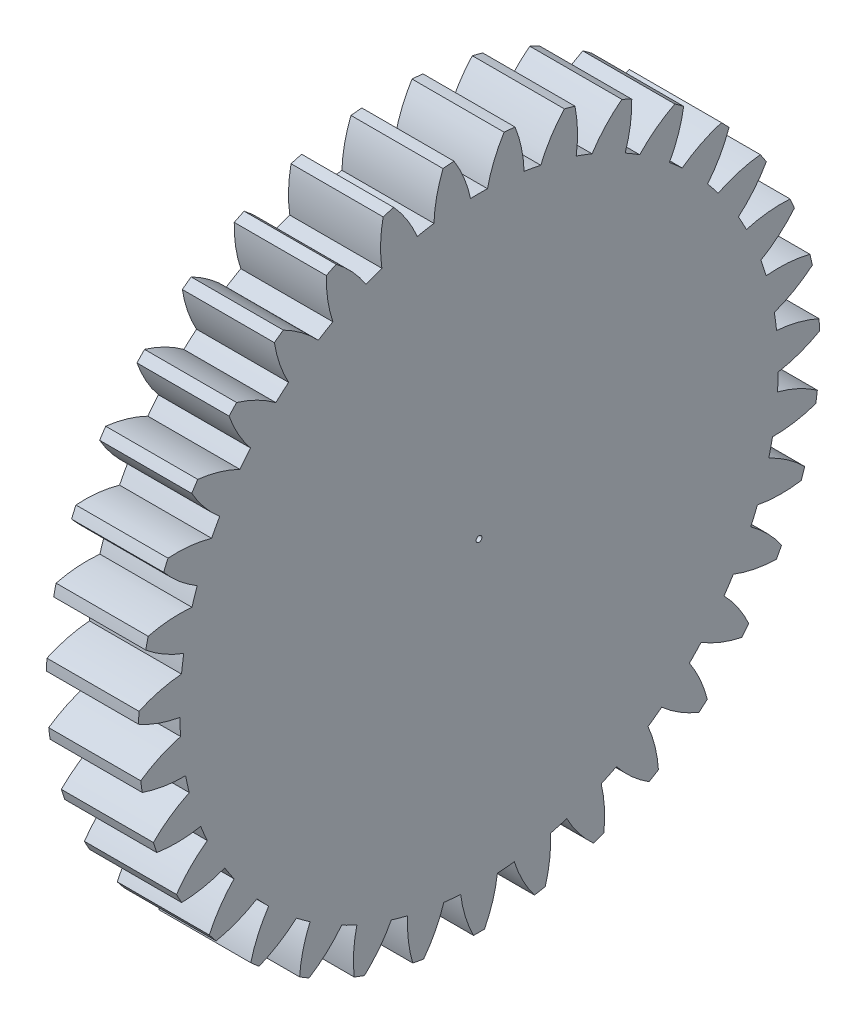
SolidWorks part; units mm, degrees
ref_plane "Plane1" through (0, 0, 0) normal (0, 0, 1) x (1, 0, 0)
ref_plane "Plane2" through (0, 0, 0) normal (0, 1, 0) x (1, 0, 0)
ref_plane "Plane3" through (0, 0, 0) normal (1, 0, 0) x (0, 0, -1)
sketch "HoldingSke" plane through (0, 0, 0) normal (0, 1, 0) x (1, 0, 0)
  line L0 (0, 0) -> (208.0646, -145.6884)
  line L1 (-15, 0) -> (100, 0) construction
  line L2 (0, 0) -> (-2.1039, 2.3779)
  line L3 (0, 0) -> (-11.863, 4.5341)
  line L4 (0, 0) -> (7.0742, 4.9534)
  line L5 (0, 0) -> (-47.5972, -17.7524)
  line L6 (0, 0) -> (-10.5278, -7.1032)
  line L7 (-2.1039, 2.3779) -> (8.8308, 51.9871)
  line L8 (-76.2, 54.61) -> (-75.184, 54.61)
  line L9 (-71.009, 38.7566) -> (-53.1078, 45.2721)
  line L10 (-76.2, 71.12) -> (104.1128, 71.12)
  line L11 (0, 0) -> (-12.7, 0)
  line L12 (-76.2, 101.6) -> (-76.0984, 101.6)
  line L13 (24.9733, 27.94) -> (52.9518, 28.4284)
  line L14 (24.9733, 27.94) -> (24.9746, 27.94)
  line L15 (24.9733, 27.94) -> (100.4006, 29.5858)
  circle A0 centre (0, 0) radius 0.3969
  circle A1 centre (0, 0) radius 38.1
  circle A2 centre (0, 0) radius 38.1
  circle A3 centre (0, 0) radius 0.3969
  dimension "MHD" = 76.2
  dimension "Hub_dia" = 76.2
  dimension "Bore" = 0.7937
  dimension "MBD" = 0.7937
  dimension "Num_teeth" = 35
  dimension "Pitch" = 254
  dimension "Overall_len" = 50.8
  dimension "Show_teeth" = 35
  dimension "Thickness" = 12.7
  dimension "OAL" = 50.8001
  dimension "T_dim" = 1.016
  dimension "Ap" = 20
  dimension "H" = 19.05
  dimension "Pitch_radius" = 180.3128
  dimension "Width" = 12.7
  dimension "Backlash" = 0.1016
  dimension "Addendum_fac" = 1
  dimension "Dedendum_fac" = 1.25
  dimension "Clearance_fac" = 0.25
  dimension "Dedendum_add" = 0.0013
sketch "BasProSke" plane through (0, 0, 0) normal (0, 1, 0) x (1, 0, 0)
  line L0 (-10, 0) -> (60, 0) construction
  line L1 (0, 0) -> (0, 46.99)
  line L2 (0, 0) -> (12.7, 0)
  line L3 (12.7, 0) -> (12.7, 46.99)
  line L4 (12.7, 46.99) -> (0, 46.99)
  dimension "Thickness" = 12.7
  dimension "Diameter" = 93.98
revolve "Base-Revolve" add sketch "BasProSke" angle 360 about L0
sketch "TooCutSke" plane through (0, 0, 0) normal (1, 0, 0) x (0, 0, -1)
  line L1 (0, 0) -> (0, 107) construction
  line L2 (0, 0) -> (-2.172, 44.3969) construction
  line L3 (0, 0) -> (-7.9623, 88.4682) construction
  line L4 (-2.172, 44.3969) -> (-3.9811, 44.2341) construction
  arc A0 (1.1677, 41.2572) -> (-1.1677, 41.2572) centre (0, 0) ccw
  arc A1 (3.4731, 46.8869) -> (-3.4731, 46.8869) centre (0, 0) ccw
  circle A2 centre (0, 0) radius 44.45 construction
  circle A3 centre (0, 0) radius 41.7693 construction
  arc A4 (-1.1677, 41.2572) -> (-3.4731, 46.8869) centre (-18.5316, 37.4334) ccw
  arc A5 (3.4731, 46.8869) -> (1.1677, 41.2572) centre (18.5316, 37.4334) ccw
  dimension "Root_dia" = 82.5475
  dimension "Overcut_dia" = 94.0308
  dimension "Pitch_dia" = 88.9
  dimension "Base_dia" = 83.5387
  dimension "Flank_rad" = 17.78
  dimension "Half_ang" = 5.143
  dimension "Half_CT" = 1.8164
extrude "ToothCut" cut sketch "TooCutSke" along normal through all
fillet "Breaks" [suppressed] radius 0.0508
fillet "RootFillets" [suppressed] radius 0.6363
pattern_circular "TeethCuts" count 35 every 10.286 about axis through (-10, 0, 0) along (1, 0, 0) of "ToothCut", "RootFillets", "Breaks"
sketch "HubNeaOneSke" plane through (0, 0, 0) normal (-1, 0, 0) x (0, 0, 1)
  circle A0 centre (0, 0) radius 38.1
  dimension "Diameter" = 76.2
extrude "HubNearOne" [suppressed] add sketch "HubNeaOneSke" along normal blind 38.1001
sketch "HubNeaBotSke" plane through (0, 0, 0) normal (-1, 0, 0) x (0, 0, 1)
  circle A0 centre (0, 0) radius 38.1
  dimension "Diameter" = 76.2
extrude "HubNearBoth" [suppressed] add sketch "HubNeaBotSke" along normal blind 19.05
ref_plane "FarPln" through (12.7, 0, 0) normal (1, 0, 0) x (0, 0, -1)
sketch "HubFarSke" plane through (12.7, 0, 0) normal (1, 0, 0) x (0, 0, -1)
  circle A0 centre (0, 0) radius 38.1
  dimension "Diameter" = 76.2
extrude "HubFar" [suppressed] add sketch "HubFarSke" along normal blind 19.05
sketch "BorSke" plane through (0, 0, 0) normal (1, 0, 0) x (0, 0, -1)
  circle A0 centre (0, 0) radius 0.3969
  dimension "Diameter" = 0.7937
extrude "Bore" cut sketch "BorSke" along normal mid plane 101.6001
sketch "KeySke" plane through (0, 0, 0) normal (1, 0, 0) x (0, 0, -1)
  line L0 (-0.127, 0) -> (-0.127, 0.6191)
  line L1 (-0.127, 0.6191) -> (0.127, 0.6191)
  line L2 (0.127, 0.6191) -> (0.127, 0)
  line L3 (0, 0) -> (0, 34) construction
  line L4 (-0.127, 0) -> (0.127, 0)
  dimension "Offset" = 0.6191
  dimension "Width" = 0.254
extrude "Keyway" [suppressed] cut sketch "KeySke" along normal mid plane 101.6001
pattern_circular "Keyway2" [suppressed] count 2 every 90 about axis through (-10, 0, 0) along (1, 0, 0)
equation "' \"Pitch@HoldingSke\" = 4"
equation "' \"Num_teeth@HoldingSke\" = 12"
equation "' \"Ap@HoldingSke\" =  20"
equation "' \"Ap@HoldingSke\" = 20"
equation "' \"Width@HoldingSke\" = 0.5"
equation "' \"Hub_dia@HoldingSke\"= 1"
equation "' \"Hub_dia@HoldingSke\" = 1"
equation "' \"Overall_len@HoldingSke\" = 1.0"
equation "' \"Bore@HoldingSke\" = 0.75"
equation "' \"T_dim@HoldingSke\" = 0.85"
equation "' \"Width@KeySke\" = 0.25"
equation "' \"Show_teeth@HoldingSke\" = 13"
equation "' \"Backlash@HoldingSke\" = 0.009"
equation "' \"Addendum_fac@HoldingSke\" = 1.0"
equation "' \"Dedendum_fac@HoldingSke\" = 1.25"
equation "' \"Dedendum_add@HoldingSke\" = 0.00005"
equation "' \"Clearance_fac@HoldingSke\" = 0.25"
equation "' \"Pitch@HoldingSke\" = 0.5"
equation "' \"Num_teeth@HoldingSke\" = 23"
equation "' \"Show_teeth@HoldingSke\" = 23"
equation "' \"Backlash@HoldingSke\" = 0.0375"
equation "\"Overcut_dia@TooCutSke\" = (\"Num_teeth@HoldingSke\" + 2 * \"Addendum_fac@HoldingSke\") / \"Pitch@HoldingSke\" + 0.002"
equation "\"Pitch_dia@TooCutSke\" = \"Num_teeth@HoldingSke\" / \"Pitch@HoldingSke\""
equation "\"Base_dia@TooCutSke\" = \"Num_teeth@HoldingSke\" / \"Pitch@HoldingSke\" * cos((\"Ap@HoldingSke\"  * 3.14159265 / 180))"
equation "\"Root_dia@TooCutSke\" = (\"Num_teeth@HoldingSke\" + 2) / \"Pitch@HoldingSke\" - 2 * (\"Addendum_fac@HoldingSke\" + \"Dedendum_fac@HoldingSke\") / \"Pitch@HoldingSke\" - \"Dedendum_add@HoldingSke\" * 2"
equation "\"Half_ang@TooCutSke\" = 180 / \"Num_teeth@HoldingSke\""
equation "\"Half_CT@TooCutSke\" = \"Num_teeth@HoldingSke\" / \"Pitch@HoldingSke\" * sin((3.14159265 / 2 / \"Num_teeth@HoldingSke\")) / 2 - 7 * \"Backlash@HoldingSke\" / 4"
equation "\"Flank_rad@TooCutSke\" = \"Num_teeth@HoldingSke\" / \"Pitch@HoldingSke\" / 5"
equation "\"Radius@RootFillets\" = \"Clearance_fac@HoldingSke\" / \"Pitch@HoldingSke\" + \"Dedendum_add@HoldingSke\""
equation "\"Break_rad@Breaks\" = 0.02 / \"Pitch@HoldingSke\""
equation "\"Thickness@HoldingSke\" = \"Width@HoldingSke\""
equation "\"OAL@HoldingSke\" = \"Thickness@HoldingSke\""
equation "\"MHD@HoldingSke\" = (\"Num_teeth@HoldingSke\" + 2) / \"Pitch@HoldingSke\" - 2 * (\"Addendum_fac@HoldingSke\" + \"Dedendum_fac@HoldingSke\")  / \"Pitch@HoldingSke\" - \"Dedendum_add@HoldingSke\" * 2"
equation "\"MBD@HoldingSke\" = (\"Num_teeth@HoldingSke\" + 2) / \"Pitch@HoldingSke\" - 2 * (\"Addendum_fac@HoldingSke\" + \"Dedendum_fac@HoldingSke\")  / \"Pitch@HoldingSke\" - \"Dedendum_add@HoldingSke\" * 2 - 0.002"
equation "\"MHD@HoldingSke\" = ((sgn( \"MHD@HoldingSke\" - \"Hub_dia@HoldingSke\" )-1)*( \"MHD@HoldingSke\" - \"Hub_dia@HoldingSke\" ))/-2+ \"Hub_dia@HoldingSke\""
equation "\"MBD@HoldingSke\" = ((sgn( \"MBD@HoldingSke\" - \"Bore@HoldingSke\" )-1)*( \"MBD@HoldingSke\" - \"Bore@HoldingSke\" ))/-2+ \"Bore@HoldingSke\""
equation "\"OAL@HoldingSke\" = ((sgn( \"OAL@HoldingSke\" - \"Overall_len@HoldingSke\" )+1)*( \"OAL@HoldingSke\" - \"Overall_len@HoldingSke\" ))/2 + \"Overall_len@HoldingSke\" + 0.000002"
equation "\"Num_teeth@TeethCuts\" = int( \"Show_teeth@HoldingSke\" ) + 1"
equation "\"Num_teeth@TeethCuts\" = ((sgn( \"Num_teeth@TeethCuts\" - \"Num_teeth@HoldingSke\" )-1)*( \"Num_teeth@TeethCuts\" - \"Num_teeth@HoldingSke\" ))/-2+ \"Num_teeth@HoldingSke\""
equation "\"Num_teeth@TeethCuts\" = ((sgn( \"Num_teeth@TeethCuts\" - 2.0)+1)*( \"Num_teeth@TeethCuts\" - 2.0))/2 +2.0"
equation "\"Angle@TeethCuts\" = 360.0 / \"Num_teeth@HoldingSke\""
equation "\"Diameter@BasProSke\" = (\"Num_teeth@HoldingSke\" + 2 * \"Addendum_fac@HoldingSke\") / \"Pitch@HoldingSke\""
equation "\"Thickness@BasProSke\"  = \"Thickness@HoldingSke\""
equation "' \"Fillet_rad@BasProSke\" =  \"Thickness@HoldingSke\" * 0.05"
equation "' \"Fillet_rad@BasProSke\" = \"Thickness@HoldingSke\" * 0.05"
equation "\"MHD@HoldingSke\" = ((sgn( \"MHD@HoldingSke\" - \"Root_dia@TooCutSke\" )-1)*( \"MHD@HoldingSke\" - \"Root_dia@TooCutSke\" ))/-2+ \"Root_dia@TooCutSke\""
equation "\"Diameter@HubNeaOneSke\" = \"MHD@HoldingSke\""
equation "\"Length@HubNearOne\" = \"OAL@HoldingSke\" - \"Thickness@BasProSke\""
equation "\"Diameter@HubNeaBotSke\" = \"MHD@HoldingSke\""
equation "\"Length@HubNearBoth\" = ( \"OAL@HoldingSke\" - \"Thickness@BasProSke\" ) / 2.0"
equation "\"Thickness@FarPln\" = \"Thickness@BasProSke\""
equation "\"Diameter@HubFarSke\" = \"MHD@HoldingSke\""
equation "\"Length@HubFar\" = ( \"OAL@HoldingSke\" - \"Thickness@BasProSke\" ) / 2.0"
equation "\"Diameter@BorSke\" = \"MBD@HoldingSke\""
equation "\"D1@Bore\" = \"OAL@HoldingSke\" * 2.0"
equation "\"D1@Keyway\" = \"OAL@HoldingSke\" * 2.0"
equation "\"Offset@KeySke\" = \"T_dim@HoldingSke\" - \"MBD@HoldingSke\" / 2.0"
